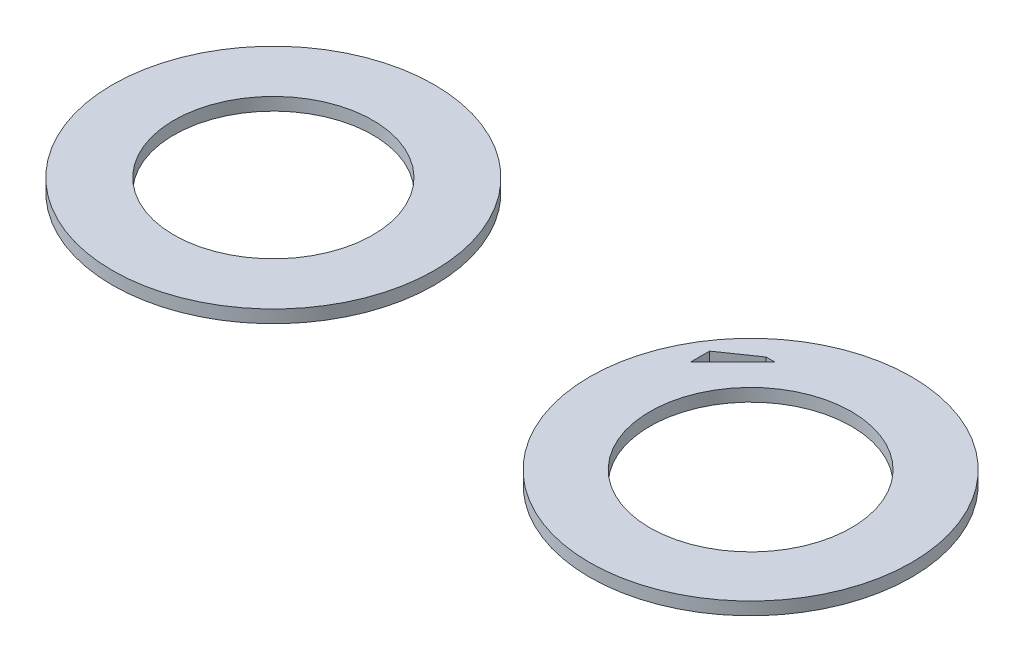
SolidWorks part; units mm, degrees
ref_plane "Front Plane" through (0, 0, 0) normal (0, 0, 1) x (1, 0, 0)
ref_plane "Top Plane" through (0, 0, 0) normal (0, 1, 0) x (1, 0, 0)
ref_plane "Right Plane" through (0, 0, 0) normal (1, 0, 0) x (0, 0, -1)
sketch "Sketch1" plane through (0, 0, 0) normal (0, 1, 0) x (1, 0, 0)
  circle A0 centre (-43.9915, 12.0987) radius 19.5
  circle A1 centre (-43.9915, 12.0987) radius 31.55
  dimension "D1" = 39
  dimension "D2" = 63.1
extrude "Boss-Extrude1" add sketch "Sketch1" along normal blind 2.5
sketch "Sketch2" plane through (0, 0, 0) normal (0, 1, 0) x (1, 0, 0)
  line L0 (28.2154, 25.4042) -> (28.2154, 21.629)
  line L1 (28.2154, 21.629) -> (36.5209, 29.9345)
  line L2 (36.5209, 29.9345) -> (34.7591, 29.9345)
  line L3 (34.7591, 29.9345) -> (28.2154, 25.4042)
  circle A0 centre (52.3768, 9.2967) radius 19.75
  circle A1 centre (52.3768, 9.2967) radius 31.55
  dimension "D1" = 39.5
  dimension "D2" = 63.1
extrude "Boss-Extrude2" add sketch "Sketch2" along normal blind 2.5 separate body
